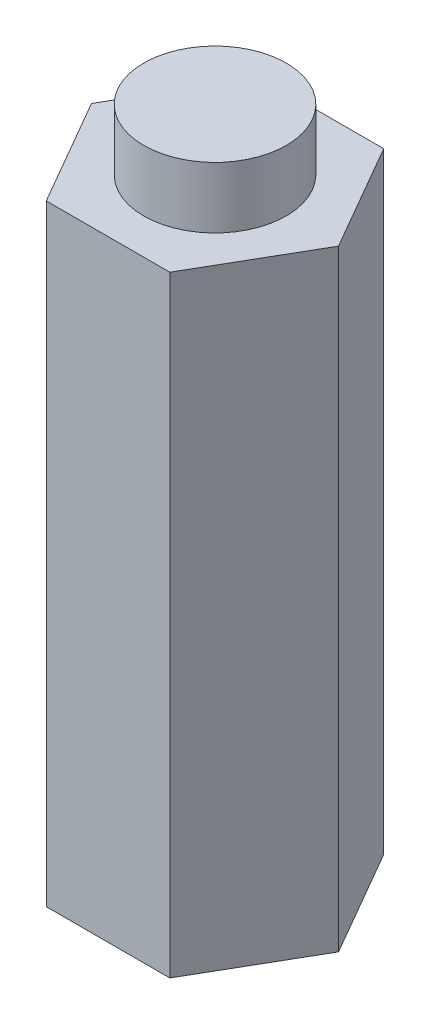
SolidWorks part; units mm, degrees
ref_plane "Płaszczyzna przednia" through (0, 0, 0) normal (0, 0, 1) x (1, 0, 0)
ref_plane "Płaszczyzna górna" through (0, 0, 0) normal (0, 1, 0) x (1, 0, 0)
ref_plane "Płaszczyzna prawa" through (0, 0, 0) normal (1, 0, 0) x (0, 0, -1)
sketch "Szkic1" plane through (0, 0, 0) normal (0, 1, 0) x (1, 0, 0)
  line L1 (12.1244, 0) -> (6.0622, 10.5)
  line L2 (6.0622, 10.5) -> (-6.0622, 10.5)
  line L3 (-6.0622, 10.5) -> (-12.1244, 0)
  line L4 (-12.1244, 0) -> (-6.0622, -10.5)
  line L5 (-6.0622, -10.5) -> (6.0622, -10.5)
  line L6 (6.0622, -10.5) -> (12.1244, 0)
  circle A0 centre (0, 0) radius 10.5 construction
  dimension "D1" = 21
  dimension "D2" = 10.5
extrude "Dodanie-wyciągnięcie1" add sketch "Szkic1" along normal blind 60
sketch "Szkic2" plane through (0, 60, 0) normal (0, 1, 0) x (1, 0, 0)
  circle A0 centre (0, 0) radius 7
  dimension "D1" = 14
extrude "Dodanie-wyciągnięcie2" add sketch "Szkic2" along normal blind 6
